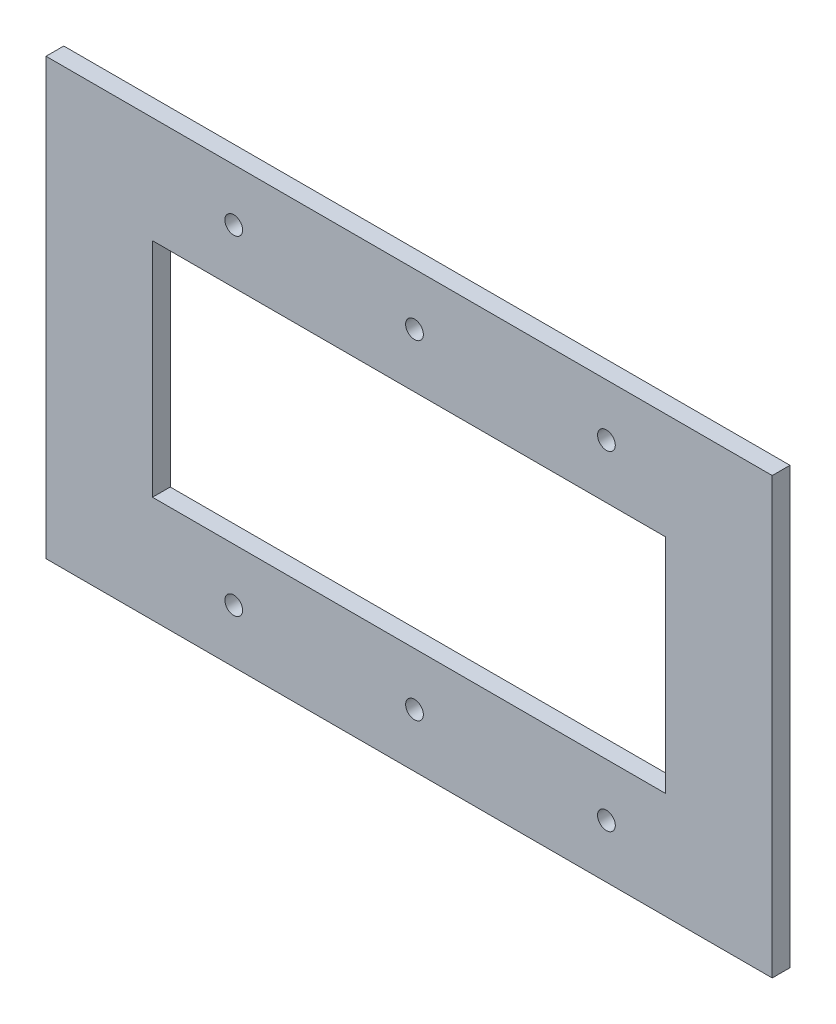
SolidWorks part; units mm, degrees
ref_plane "Front Plane" through (0, 0, 0) normal (0, 0, 1) x (1, 0, 0)
ref_plane "Top Plane" through (0, 0, 0) normal (0, 1, 0) x (1, 0, 0)
ref_plane "Right Plane" through (0, 0, 0) normal (1, 0, 0) x (0, 0, -1)
sketch "Sketch1" plane through (0, 0, 0) normal (0, 0, 1) x (1, 0, 0)
  line L0 (-38.1, 117.602) -> (221.742, 117.602)
  line L1 (0, 0) -> (183.642, 0)
  line L2 (0, 0) -> (0, 79.502)
  line L3 (0, 79.502) -> (183.642, 79.502)
  line L4 (183.642, 0) -> (183.642, 79.502)
  line L5 (-38.1, -38.1) -> (221.742, -38.1)
  line L6 (221.742, 117.602) -> (221.742, -38.1)
  line L7 (-38.1, 117.602) -> (-38.1, -38.1)
  dimension "D1" = 183.642
  dimension "D2" = 79.502
  dimension "D4" = 38.1
  dimension "D5" = 38.1
  dimension "D6" = 38.1
extrude "Boss-Extrude1" add sketch "Sketch1" along normal blind 6.35
hole_wizard "1/4 (0.25) Diameter Slot1" positions "Sketch3" profile "Sketch2" size "1/4" standard "ANSI Inch" slot yes end condition through all
sketch "Sketch3" plane through (0, 0, 6.35) normal (0, 0, 1) x (1, 0, 0)
  point P0 (29.0675, 98.9075)
  point P2 (93.7403, 98.9075)
  point P4 (162.4144, 98.9075)
  point P6 (162.4144, -18.9164)
  point P8 (93.7403, -18.9164)
  point P10 (29.0675, -18.9164)
sketch "Sketch2" plane through (29.0675, 98.9075, 6.35) normal (1, 0, 0) x (0, -1, 0)
  line L0 (0, 0) -> (0, 6.35)
  line L1 (0, 6.35) -> (3.175, 6.35)
  line L2 (3.175, 6.35) -> (3.175, 0)
  line L5 (3.175, 0) -> (0, 0)
  line L11 (0, -6.35) -> (0, 107.95) construction
  dimension "Thru Hole Dia." = 6.35
  dimension "Thru Hole Depth" = 6.35
